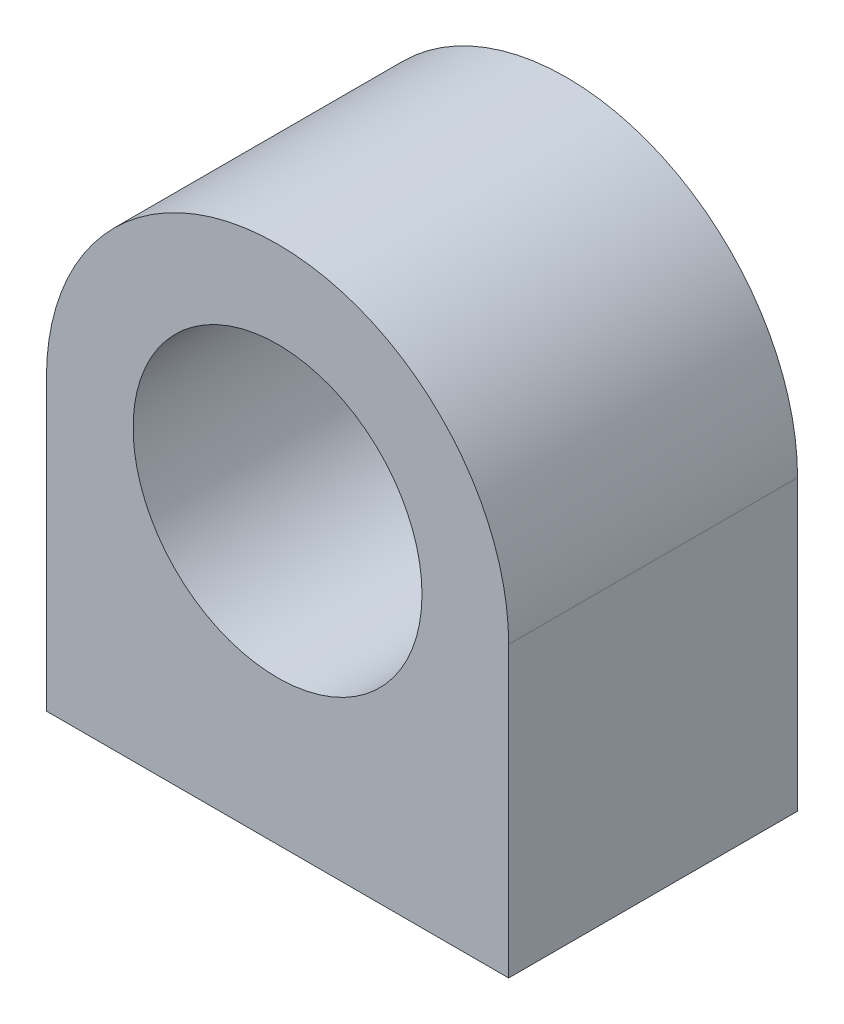
SolidWorks part; units mm, degrees
material "6061 Alloy"
ref_plane "Front Plane" through (0, 0, 0) normal (0, 0, 1) x (1, 0, 0)
ref_plane "Top Plane" through (0, 0, 0) normal (0, 1, 0) x (1, 0, 0)
ref_plane "Right Plane" through (0, 0, 0) normal (1, 0, 0) x (0, 0, -1)
sketch "Sketch1" plane through (0, 0, 0) normal (0, 0, 1) x (1, 0, 0)
  line L0 (-4, 0) -> (4, 0)
  line L1 (4, 0) -> (4, 5)
  line L2 (-4, 5) -> (-4, 0)
  arc A0 (4, 5) -> (-4, 5) centre (0, 5) ccw
  circle A1 centre (0, 5) radius 2.5
  point P5 (0, 0)
  dimension "D3" = 5
  dimension "D1" = 8
  dimension "D2" = 5
extrude "Boss-Extrude1" add sketch "Sketch1" along normal mid plane 5
